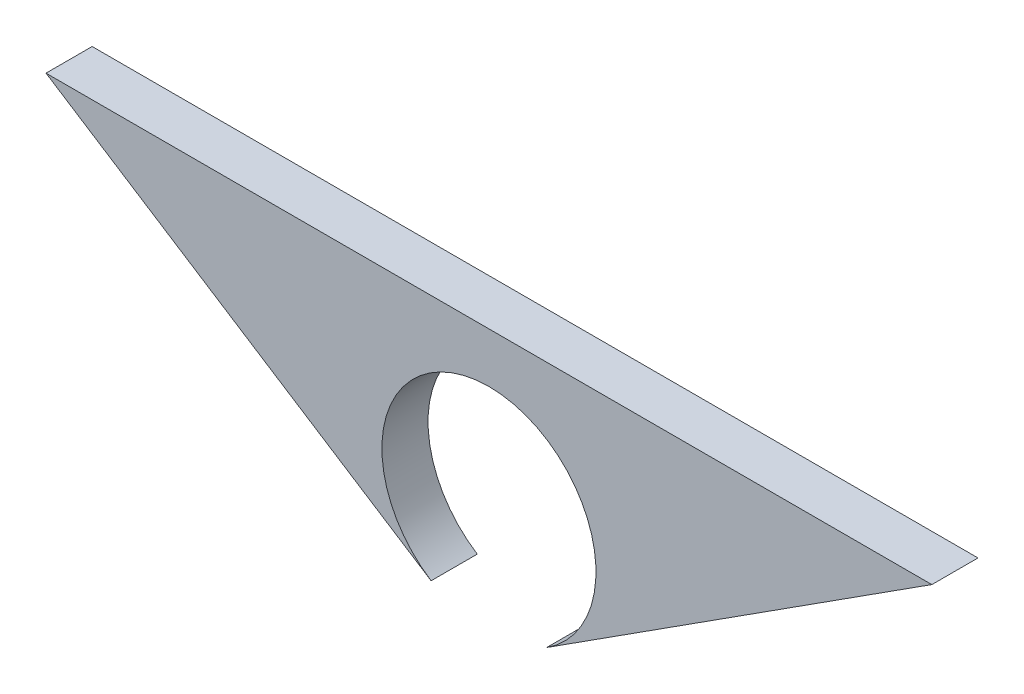
SolidWorks part; units mm, degrees
material "Teak"
ref_plane "Front Plane" through (0, 0, 0) normal (0, 0, 1) x (1, 0, 0)
ref_plane "Top Plane" through (0, 0, 0) normal (0, 1, 0) x (1, 0, 0)
ref_plane "Right Plane" through (0, 0, 0) normal (1, 0, 0) x (0, 0, -1)
sketch "Sketch1" plane through (0, 0, 0) normal (0, 0, 1) x (1, 0, 0)
  line L0 (-15.24, 5.4) -> (15.24, 5.4)
  line L1 (0, 0) -> (0, 13.6151) construction
  line L2 (-15.24, 5.4) -> (-1.9885, -3.1001)
  line L3 (15.24, 5.4) -> (1.9885, -3.1001)
  arc A0 (1.9885, -3.1001) -> (-1.9885, -3.1001) centre (0, 0) ccw
  point P5 (0, 5.4)
  dimension "D1" = 7.366
  dimension "D2" = 30.48
  dimension "D3" = 5.4
extrude "Boss-Extrude1" add sketch "Sketch1" along normal blind 1.5875
